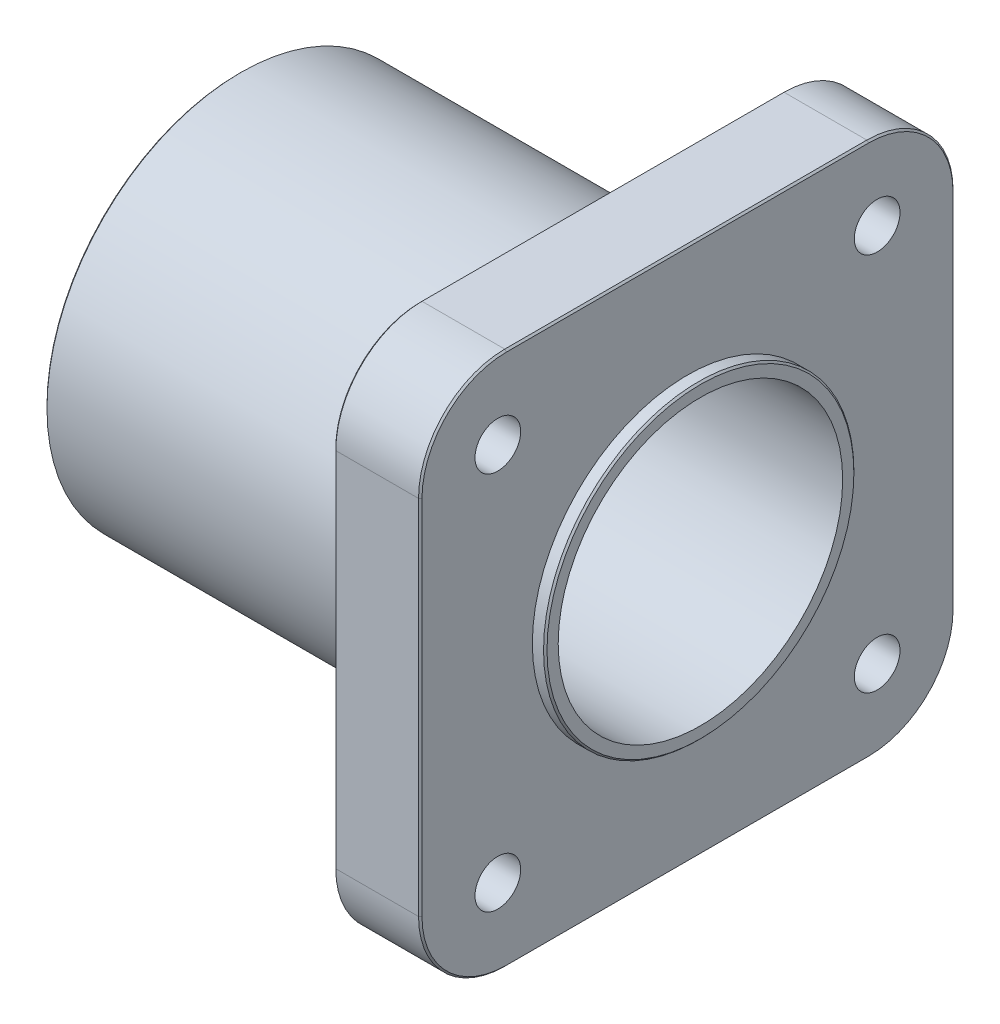
SolidWorks part; units mm, degrees
material "Alliage 1060"
ref_plane "Plan de face" through (0, 0, 0) normal (0, 0, 1) x (1, 0, 0)
ref_plane "Plan de dessus" through (0, 0, 0) normal (0, 1, 0) x (1, 0, 0)
ref_plane "Plan de droite" through (0, 0, 0) normal (1, 0, 0) x (0, 0, -1)
sketch "Esquisse1" plane through (0, 0, 0) normal (0, 0, 1) x (1, 0, 0)
  line L0 (-138.8311, 0) -> (275.2383, 0) construction
  line L1 (0, 15) -> (0, 22.5)
  line L2 (0, 22.5) -> (52, 22.5)
  line L3 (0, 15) -> (5, 15)
  line L8 (52, 22.5) -> (52, 16.5)
  line L9 (5, 15) -> (5, 16)
  line L10 (5, 16) -> (15, 16)
  line L11 (15, 16) -> (15, 16.5)
  line L12 (15, 16.5) -> (52, 16.5)
  point P8 (5, 15.5)
  dimension "D1" = 32
  dimension "D2" = 30
  dimension "D3" = 5
  dimension "D4" = 10
  dimension "D5" = 37
  dimension "D6" = 45
  dimension "D7" = 33
revolve "Révolution1" add sketch "Esquisse1" angle 360 about L0
sketch "Esquisse2" plane through (52, 0, 0) normal (1, 0, 0) x (0, 0, -1)
  line L1 (-31, 31) -> (31, 31)
  line L2 (-31, 31) -> (-31, -31)
  line L3 (-31, -31) -> (31, -31)
  line L4 (31, 31) -> (31, -31)
  line L5 (-31, 31) -> (31, -31) construction
  line L6 (-31, -31) -> (31, 31) construction
  circle A0 centre (0, 0) radius 16.5
  circle A1 centre (0, 0) radius 16.5 construction
  point P0 (0, 0)
  dimension "D1" = 62
  dimension "D2" = 62
extrude "Boss.-Extru.1" add sketch "Esquisse2" against normal blind 10
fillet "Congé1" radius 10 4 edges at (47, -31, 31) (47, -31, -31) (47, 31, -31) (47, 31, 31)
hole_wizard "Dégagement M51" positions "Esquisse3" profile "Esquisse4" hole size "M5" standard "ISO" end condition through all
sketch "Esquisse3" plane through (52, 0, 0) normal (1, 0, 0) x (0, 0, -1)
  line L0 (40.039, 0) -> (-43.0354, 0) construction
  line L2 (0, 52.9634) -> (0, -52.2958) construction
  point P0 (22, 22)
  dimension "D1" = 22
  dimension "D2" = 22
sketch "Esquisse4" plane through (52, 22, -22) normal (0, 1, 0) x (0, 0, -1)
  line L0 (0, 0) -> (0, 52)
  line L1 (0, 52) -> (2.65, 52)
  line L2 (2.65, 52) -> (2.65, 0)
  line L5 (2.65, 0) -> (0, 0)
  line L11 (0, -6.35) -> (0, 107.95) construction
  dimension "Diamètre du perçage jusqu'au prochain" = 5.3
  dimension "Profondeur du perçage jusqu'au prochain" = 52
mirror "Symétrie1" about plane through (0, 0, 0) normal (0, 0, 1) of "Dégagement M51"
mirror "Symétrie2" about plane through (0, 0, 0) normal (0, 1, 0) of "Symétrie1", "Dégagement M51"
fillet "Congé2" radius 4 1 edges at (42, 0, -22.5)
sketch "Esquisse5" plane through (52, 0, 0) normal (1, 0, 0) x (0, 0, -1)
  circle A0 centre (0, 0) radius 18
  circle A1 centre (0, 0) radius 16.5
  circle A2 centre (0, 0) radius 16.5 construction
  dimension "D1" = 36
extrude "Boss.-Extru.2" add sketch "Esquisse5" along normal blind 1.5
chamfer "Chanfrein1" distance 0.2 angle 45 1 edges at (53.5, 0, -18)
chamfer "Chanfrein2" distance 0.2 angle 45 8 edges at (52, 28.0711, -28.0711) (52, 0, -31) (52, -28.0711, -28.0711) (52, -31, 0) (52, -28.0711, 28.0711) (52, 0, 31) (52, 31, 0) (52, 28.0711, 28.0711)
chamfer "Chanfrein3" distance 0.2 angle 45 8 edges at (42, 28.0711, -28.0711) (42, 0, -31) (42, -28.0711, -28.0711) (42, -31, 0) (42, -28.0711, 28.0711) (42, 0, 31) (42, 28.0711, 28.0711) (42, 31, 0)
chamfer "Chanfrein4" distance 0.2 angle 45 2 edges at (0, 0, 22.5) (0, 0, 15)
